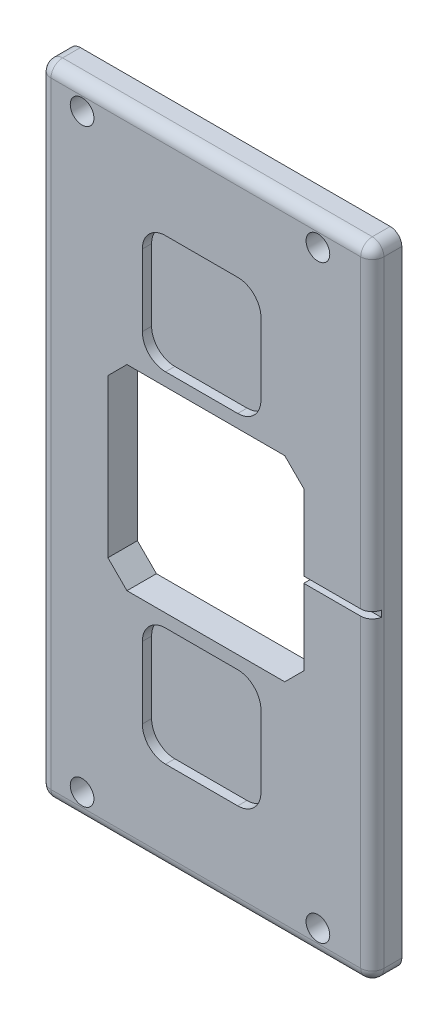
SolidWorks part; units mm, degrees
ref_plane "Front Plane" through (0, 0, 0) normal (0, 0, 1) x (1, 0, 0)
ref_plane "Top Plane" through (0, 0, 0) normal (0, 1, 0) x (1, 0, 0)
ref_plane "Right Plane" through (0, 0, 0) normal (1, 0, 0) x (0, 0, -1)
sketch "Sketch1" plane through (0, 0, 0) normal (0, 0, 1) x (1, 0, 0)
  line L0 (68.0566, 68.87) -> (126.0194, 68.87)
  line L22 (62.2146, 68.87) -> (68.0566, 68.87)
  line L28 (62.2146, -68.87) -> (126.0194, -68.87)
  line L31 (126.0194, -68.87) -> (126.0194, 68.87)
  line L38 (62.2146, 68.87) -> (54.2999, 68.87)
  line L40 (62.2146, -68.87) -> (54.2999, -68.87)
  line L41 (54.2999, 68.87) -> (54.2999, -68.87)
extrude "Boss-Extrude3" add sketch "Sketch1" along normal blind 6.35
ref_plane "Plane1" through (0, 0, 0) normal (0, -1, 0) x (-1, 0, 0)
sketch "Sketch6" plane through (0, 0, 0) normal (0, 0, -1) x (-1, 0, 0)
  circle A8 centre (-114.3, -63.5) radius 2.5527
  circle A9 centre (-63.5, -63.5) radius 2.5527
  circle A14 centre (-63.5, 63.5) radius 2.5527
  circle A15 centre (-114.3, 63.5) radius 2.5527
extrude "Cut-Extrude5" cut sketch "Sketch6" against normal up to surface (6.35 mm away) up to face at (90.1597, 0, 6.35)
fillet "Fillet2" radius 2.5 8 edges at (54.2999, 68.87, 3.175) (54.2999, -68.87, 3.175) (126.0194, -68.87, 3.175) (126.0194, 68.87, 3.175) (90.1597, 68.87, 6.35) (90.1597, -68.87, 6.35) (54.2999, 0, 6.35) (126.0194, 0, 6.35)
sketch "Sketch7" plane through (0, 0, 6.35) normal (0, 0, 1) x (1, 0, 0)
  line L0 (90.1597, -66.37) -> (90.1597, 66.37) construction
  line L3 (56.7999, -66.37) -> (123.5194, -66.37) construction
  line L5 (123.5194, 66.37) -> (56.7999, 66.37) construction
  line L6 (56.7999, 0) -> (123.5194, 0) construction
  line L7 (56.7999, 66.37) -> (56.7999, -66.37) construction
  line L8 (123.5194, -66.37) -> (123.5194, 66.37) construction
  circle A0 centre (90.1597, 0) radius 3.43
  dimension "D1" = 6.86
extrude "Cut-Extrude6" cut sketch "Sketch7" against normal through all
sketch "Sketch10" plane through (0, 0, 6.35) normal (0, 0, 1) x (1, 0, 0)
  line L14 (69.065, 21.0947) -> (111.2544, 21.0947)
  line L15 (69.065, 21.0947) -> (69.065, -21.0947)
  line L16 (69.065, -21.0947) -> (111.2544, -21.0947)
  line L17 (111.2544, 21.0947) -> (111.2544, -21.0947)
extrude "Cut-Extrude8" cut sketch "Sketch10" against normal through all
sketch "Sketch11" plane through (0, 0, 6.35) normal (0, 0, 1) x (1, 0, 0)
  line L0 (123.5194, -66.37) -> (123.5194, 66.37) construction
  line L1 (123.5194, -0.667) -> (111.2544, -0.667)
  line L3 (123.5194, 0.6842) -> (111.2544, 0.6842)
  line L4 (111.2544, -0.667) -> (111.2544, 0.6842)
  line L5 (111.2544, -21.0947) -> (111.2544, 21.0947) construction
  line L7 (123.5194, -0.667) -> (127.3985, -0.667)
  line L9 (123.5194, 0.6842) -> (127.3985, 0.6842)
  line L10 (127.3985, -0.667) -> (127.3985, 0.6842)
extrude "Cut-Extrude9" cut sketch "Sketch11" against normal blind 2
sketch "Sketch12" plane through (0, 0, 6.35) normal (0, 0, 1) x (1, 0, 0)
  line L0 (76.4742, -44.3) -> (76.4742, -50.9707) construction
  line L1 (81.4742, -49.3) -> (76.4742, -49.3) construction
  line L2 (96.8742, -23.9) -> (102.0243, -23.9) construction
  line L3 (102.0243, -23.9) -> (101.8742, -28.9) construction
  line L5 (76.4742, -49.3) -> (102.0243, -49.3)
  line L6 (76.4742, -49.3) -> (76.4742, -23.9)
  line L7 (76.4742, -23.9) -> (102.0243, -23.9)
  line L8 (102.0243, -49.3) -> (102.0243, -23.9)
extrude "Cut-Extrude10" cut sketch "Sketch12" against normal blind 2
fillet "Fillet3" radius 5 4 edges at (102.0243, -23.9, 5.35) (76.4742, -23.9, 5.35) (76.4742, -49.3, 5.35) (102.0243, -49.3, 5.35)
mirror "Mirror1" about plane through (0, 0, 0) normal (0, -1, 0) of "Fillet3", "Cut-Extrude10"
chamfer "Chamfer1" distance 4.1 angle 45 4 edges at (69.065, -21.0947, 3.175) (69.065, 21.0947, 3.175) (111.2544, 21.0947, 3.175) (111.2544, -21.0947, 3.175)
